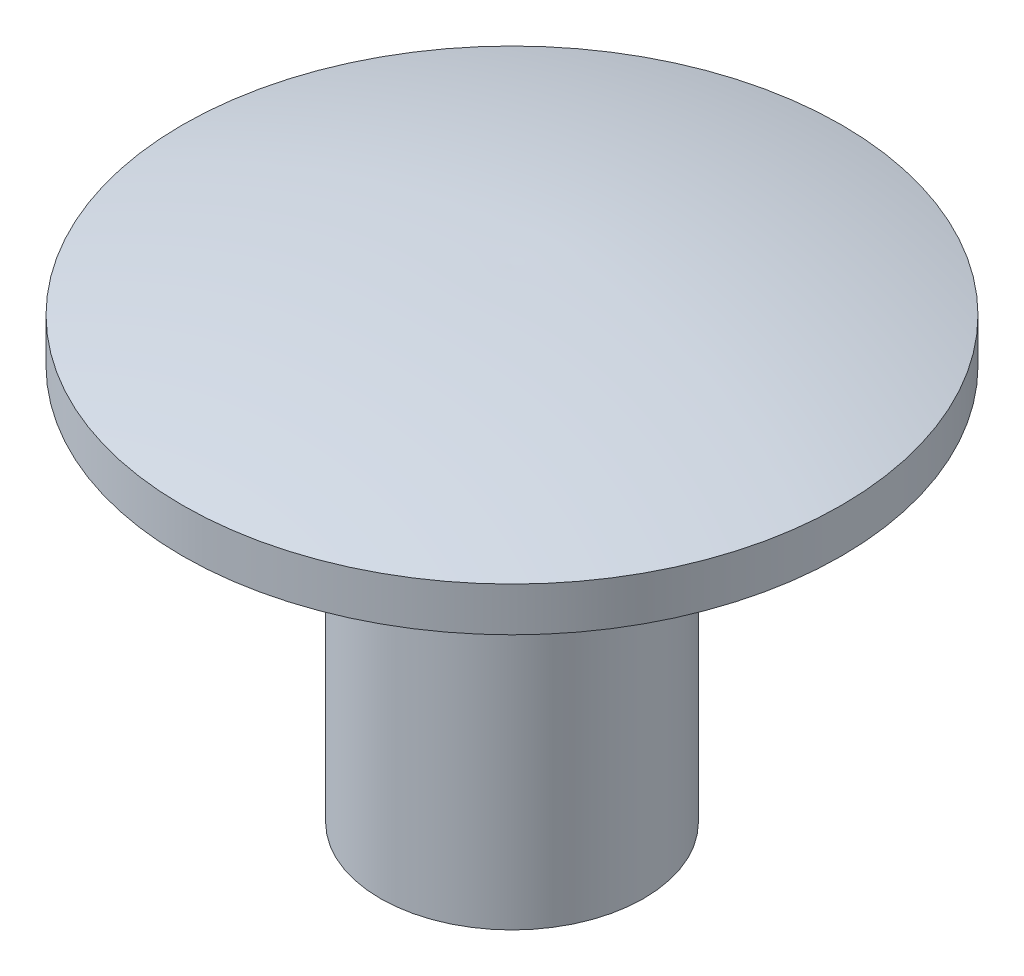
SolidWorks part; units mm, degrees
material "Copper"
ref_plane "Front Plane" through (0, 0, 0) normal (0, 0, 1) x (1, 0, 0)
ref_plane "Top Plane" through (0, 0, 0) normal (0, 1, 0) x (1, 0, 0)
ref_plane "Right Plane" through (0, 0, 0) normal (1, 0, 0) x (0, 0, -1)
sketch "Sketch1" plane through (0, 0, 0) normal (0, 1, 0) x (1, 0, 0)
  circle A0 centre (0, 0) radius 7.5
  dimension "D1" = 15
extrude "Boss-Extrude1" add sketch "Sketch1" along normal blind 1
sketch "Sketch2" plane through (0, 0, 0) normal (0, 0, 1) x (1, 0, 0)
  line L0 (0, 1) -> (0, 2)
  line L1 (7.5, 1) -> (-7.5, 1) construction
  line L2 (0, 1) -> (7.5, 1)
  spline S0 degree 2 poles (7.5, 1) (3.8228, 2.0476) (0, 2) knots 0 0 0 1 1 1
revolve "Revolve1" add sketch "Sketch2" angle 360 about L0
sketch "Sketch3" plane through (0, 0, 0) normal (0, -1, 0) x (1, 0, 0)
  line L1 (-3, 3) -> (3, 3)
  line L2 (-3, 3) -> (-3, -3)
  line L3 (-3, -3) -> (3, -3)
  line L4 (3, 3) -> (3, -3)
  line L5 (-3, 3) -> (3, -3) construction
  line L6 (-3, -3) -> (3, 3) construction
  point P0 (0, 0)
extrude "Boss-Extrude2" add sketch "Sketch3" along normal blind 2
sketch "Sketch4" plane through (0, -2, 0) normal (0, -1, 0) x (1, 0, 0)
  circle A0 centre (0, 0) radius 3
extrude "Boss-Extrude3" add sketch "Sketch4" along normal blind 7
hole_wizard "M5 Tapped Hole2" positions "Sketch5" profile "Sketch6" tap size "M5" standard "ISO"
sketch "Sketch5" plane through (0, -9, 0) normal (0, -1, 0) x (-1, 0, 0)
  point P0 (0, 0)
sketch "Sketch6" plane through (0, -9, 0) normal (1, 0, 0) x (0, 0, -1)
  line L0 (0, 0) -> (0, 8.2608)
  line L1 (0, 8.2608) -> (2.1, 6.999)
  line L2 (2.1, 6.999) -> (2.1, 0)
  line L5 (2.1, 0) -> (0, 0)
  line L10 (0, 8.2608) -> (-2.1, 6.999) construction
  line L11 (0, -6.35) -> (0, 107.95) construction
  dimension "Tap Drill Dia." = 4.2
  dimension "Tap Drill Depth" = 6.999
  dimension "Drill Angle" = 118
cosmetic thread "Hole Thread1" parameters "D1"=10, "D2"=5
